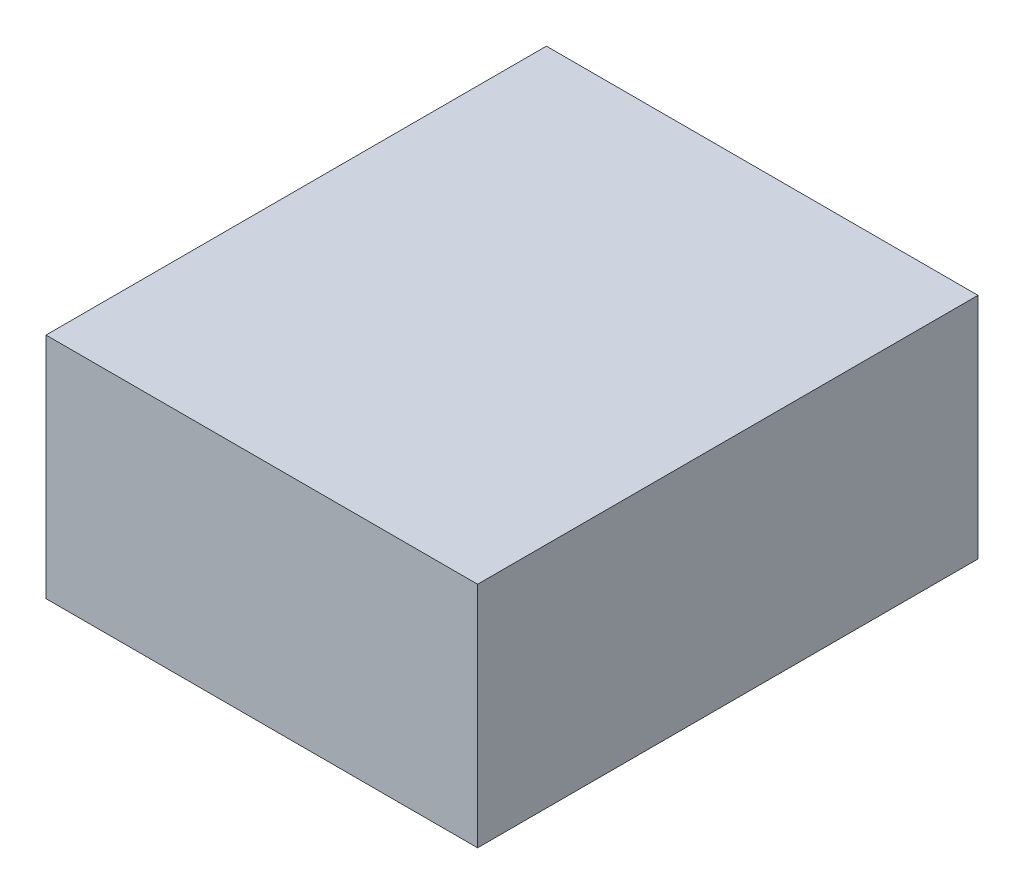
SolidWorks part; units mm, degrees
ref_plane "Front Plane" through (0, 0, 0) normal (0, 0, 1) x (1, 0, 0)
ref_plane "Top Plane" through (0, 0, 0) normal (0, 1, 0) x (1, 0, 0)
ref_plane "Right Plane" through (0, 0, 0) normal (1, 0, 0) x (0, 0, -1)
sketch "Sketch1" plane through (0, 0, 0) normal (0, 0, 1) x (1, 0, 0)
  line L0 (0, 0) -> (3.175, 0)
  line L1 (3.175, 0) -> (3.175, 101.6)
  line L2 (3.175, 101.6) -> (434.975, 101.6)
  line L3 (434.975, 101.6) -> (434.975, -127)
  line L4 (434.975, -127) -> (438.15, -127)
  line L5 (438.15, -127) -> (438.15, 104.775)
  line L6 (438.15, 104.775) -> (0, 104.775)
  line L7 (0, 104.775) -> (0, 0)
  line L8 (3.175, 101.6) -> (3.175, 104.775) construction
  point P8 (438.15, -7.042)
  dimension "D1" = 3.175
  dimension "D2" = 431.8
  dimension "D3" = 101.6
  dimension "D4" = 228.6
extrude "Boss-Extrude1" add sketch "Sketch1" along normal blind 508
sketch "Sketch2" plane through (0, 0, 0) normal (-1, 0, 0) x (0, 0, 1)
  line L0 (508, 0) -> (0, 0) construction
  line L1 (139.7, -76.2) -> (165.1, -76.2)
  line L2 (508, 101.6) -> (508, -127) construction
  line L3 (508, -76.2) -> (508, 0)
  line L4 (63.5, 0) -> (508, 0)
  line L5 (0, 104.775) -> (0, 0) construction
  line L6 (165.1, -76.2) -> (165.1, -127)
  line L7 (508, -127) -> (0, -127) construction
  line L8 (165.1, -127) -> (508, -127)
  line L9 (508, -127) -> (508, -76.2)
  arc A0 (63.5, 0) -> (139.7, -76.2) centre (63.5, -76.2) cw
  point P17 (0, 0)
  point P18 (138.5044, -75.0044)
  point P19 (0, 0)
  dimension "D1" = 76.2
  dimension "D2" = 63.5
  dimension "D3" = 25.4
extrude "Boss-Extrude2" add sketch "Sketch2" against normal up to surface (3.175 mm away) up to face at (3.175, 50.8, 254)
sketch "Sketch3" plane through (0, 0, 508) normal (0, 0, 1) x (1, 0, 0)
  line L1 (0, 104.775) -> (438.15, 104.775)
  line L2 (0, 104.775) -> (0, -127)
  line L3 (0, -127) -> (438.15, -127)
  line L4 (438.15, 104.775) -> (438.15, -127)
extrude "Boss-Extrude3" add sketch "Sketch3" against normal blind 3.175
